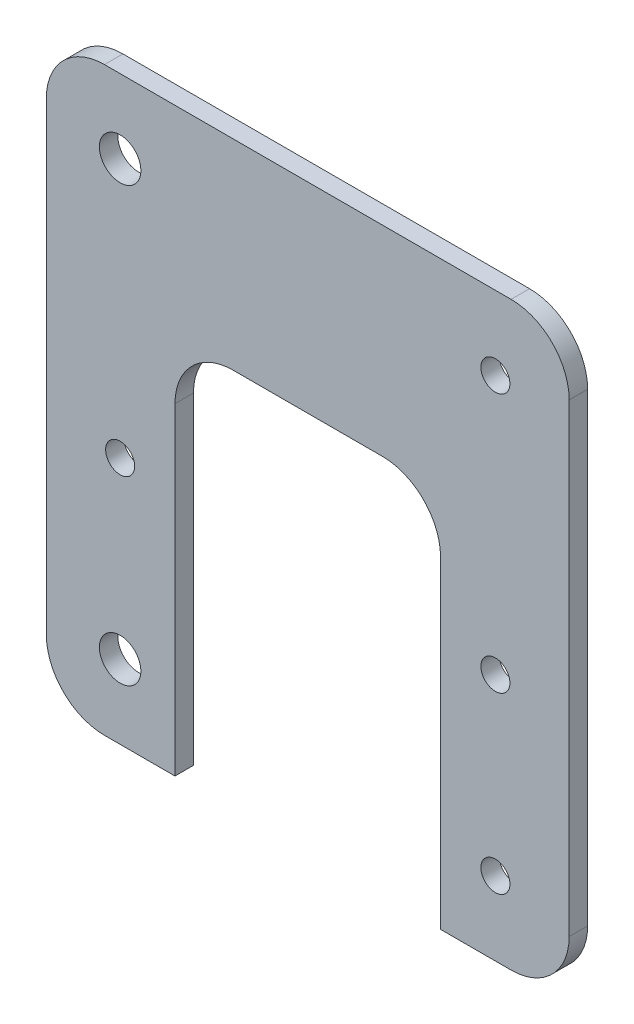
SolidWorks part; units mm, degrees
ref_plane "Front Plane" through (0, 0, 0) normal (0, 0, 1) x (1, 0, 0)
ref_plane "Top Plane" through (0, 0, 0) normal (0, 1, 0) x (1, 0, 0)
ref_plane "Right Plane" through (0, 0, 0) normal (1, 0, 0) x (0, 0, -1)
sketch "Sketch1" plane through (0, 0, 0) normal (0, 0, 1) x (1, 0, 0)
  line L0 (35, 45) -> (-35, 45) construction
  line L1 (-45, -55) -> (45, -55)
  line L2 (-45, -55) -> (-45, 45)
  line L3 (-45, 45) -> (45, 45)
  line L4 (45, -55) -> (45, 45)
  line L5 (-43.1231, -55) -> (43.1231, -55) construction
  line L6 (-45, 35) -> (-45, 25) construction
  line L7 (45, 25) -> (45, 35) construction
  circle A0 centre (32.3, -12.3) radius 2.5 construction
  circle A1 centre (32.3, -42.3) radius 2.5 construction
  circle A2 centre (-32.3, -42.3) radius 3.57 construction
  circle A3 centre (-32.3, -12.3) radius 2.5 construction
  circle A4 centre (32.3, -12.3) radius 2.5
  circle A5 centre (32.3, -42.3) radius 2.5
  circle A6 centre (-32.3, -42.3) radius 3.57
  circle A7 centre (-32.3, -12.3) radius 2.5
  circle A8 centre (-32.3, 32.3) radius 3.57 construction
  circle A9 centre (-32.3, 32.3) radius 3.57
  circle A10 centre (32.3, 32.3) radius 2.5 construction
  circle A11 centre (32.3, 32.3) radius 2.5
extrude "Boss-Extrude1" add sketch "Sketch1" against normal blind 3.18 from offset 19.16
sketch "Sketch2" plane through (0, 0, 15.98) normal (0, 0, -1) x (-1, 0, 0)
  line L0 (45, -55) -> (-45, -55) construction
  line L1 (-22.86, -55) -> (22.86, -55)
  line L2 (-22.86, -55) -> (-22.86, 10.5119)
  line L3 (-22.86, 10.5119) -> (22.86, 10.5119)
  line L4 (22.86, -55) -> (22.86, 10.5119)
  line L5 (0, 0) -> (0, 10.5119) construction
  dimension "D1" = 45.72
extrude "Cut-Extrude1" cut sketch "Sketch2" against normal through all
fillet "Fillet1" radius 10 6 edges at (45, -55, 17.57) (-45, -55, 17.57) (-45, 45, 17.57) (45, 45, 17.57) (-22.86, 10.5119, 17.57) (22.86, 10.5119, 17.57)
ref_plane "Midplane" through (0, -5, 0) normal (0, 1, 0) x (1, 0, 0)
